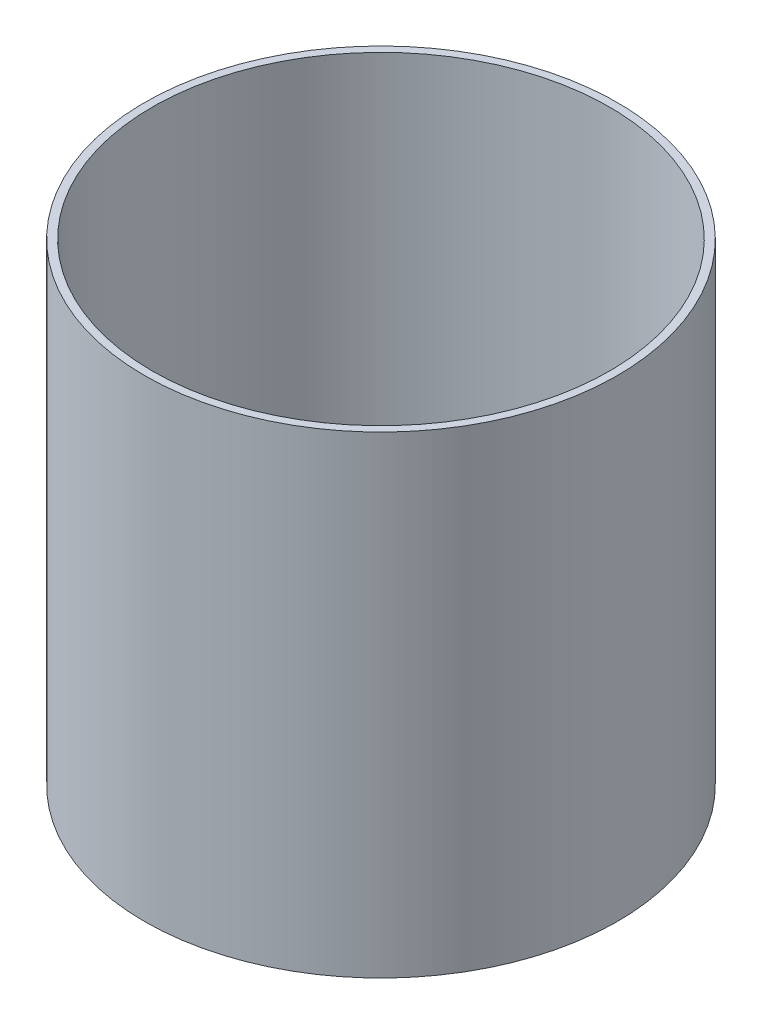
SolidWorks part; units mm, degrees
ref_plane "Front Plane" through (0, 0, 0) normal (0, 0, 1) x (1, 0, 0)
ref_plane "Top Plane" through (0, 0, 0) normal (0, 1, 0) x (1, 0, 0)
ref_plane "Right Plane" through (0, 0, 0) normal (1, 0, 0) x (0, 0, -1)
sketch "Sketch1" plane through (0, 0, 0) normal (0, 1, 0) x (1, 0, 0)
  circle A0 centre (0, 0) radius 76
  circle A1 centre (0, 0) radius 73.5
extrude "Boss-Extrude1" add sketch "Sketch1" along normal blind 152
